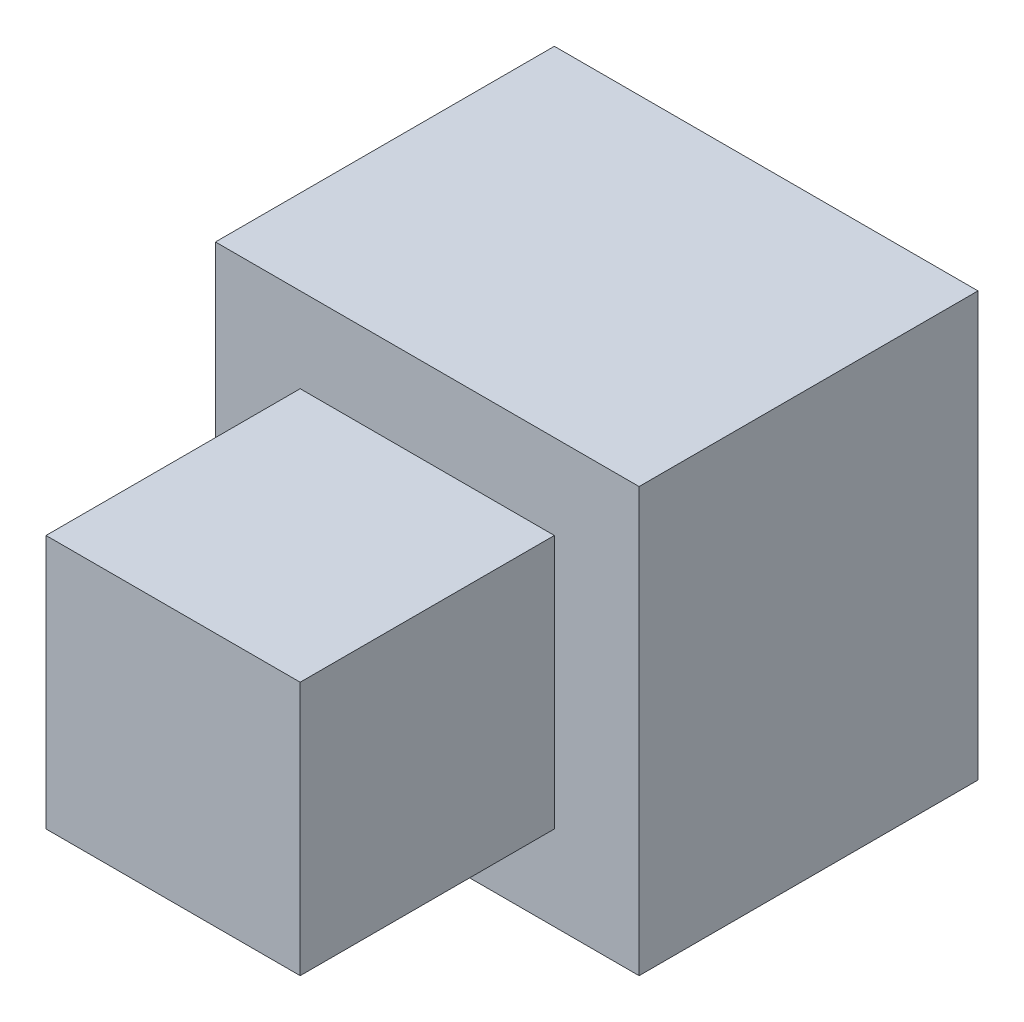
SolidWorks part; units mm, degrees
ref_plane "前视基准面" through (0, 0, 0) normal (0, 0, 1) x (1, 0, 0)
ref_plane "上视基准面" through (0, 0, 0) normal (0, 1, 0) x (1, 0, 0)
ref_plane "右视基准面" through (0, 0, 0) normal (1, 0, 0) x (0, 0, -1)
sketch "草图1" plane through (0, 0, 0) normal (0, 0, 1) x (1, 0, 0)
  line L1 (-25, -25) -> (25, -25)
  line L2 (-25, -25) -> (-25, 25)
  line L3 (-25, 25) -> (25, 25)
  line L4 (25, -25) -> (25, 25)
  line L5 (0, 25) -> (0, -25) construction
  line L6 (-25, 0) -> (25, 0) construction
  point P0 (0, 0)
  dimension "D1" = 50
  dimension "D2" = 50
extrude "凸台-拉伸1" add sketch "草图1" along normal blind 40
sketch "草图2" plane through (0, 0, 40) normal (0, 0, 1) x (1, 0, 0)
  line L1 (-15, -15) -> (15, -15)
  line L2 (-15, -15) -> (-15, 15)
  line L3 (-15, 15) -> (15, 15)
  line L4 (15, -15) -> (15, 15)
  line L5 (0, 15) -> (0, -15) construction
  line L6 (-15, 0) -> (15, 0) construction
  point P0 (0, 0)
  dimension "D1" = 30
  dimension "D2" = 30
extrude "凸台-拉伸2" add sketch "草图2" along normal blind 30
